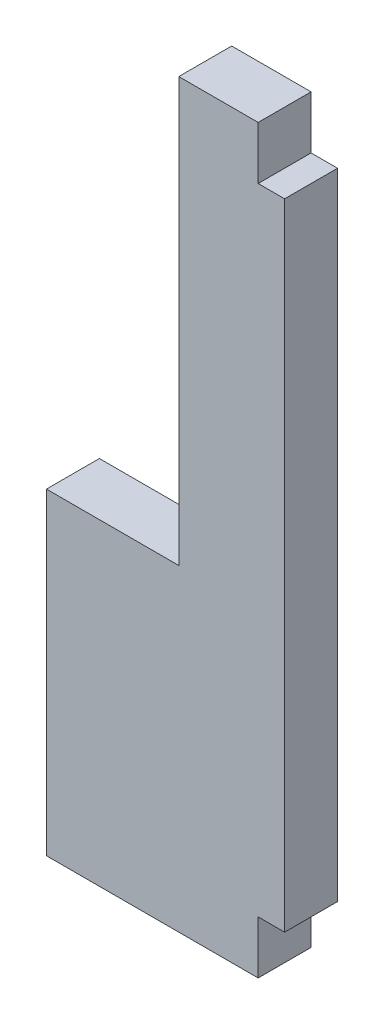
SolidWorks part; units mm, degrees
ref_plane "Front Plane" through (0, 0, 0) normal (0, 0, 1) x (1, 0, 0)
ref_plane "Top Plane" through (0, 0, 0) normal (0, 1, 0) x (1, 0, 0)
ref_plane "Right Plane" through (0, 0, 0) normal (1, 0, 0) x (0, 0, -1)
sketch "Sketch2" plane through (0, 0, 0) normal (0, 0, 1) x (1, 0, 0)
  line L0 (0, 120) -> (-5, 120)
  line L1 (-5, 120) -> (-5, 130)
  line L2 (-5, 130) -> (-20, 130)
  line L3 (-20, 130) -> (-20, 50)
  line L4 (-20, 50) -> (-45, 50)
  line L5 (-45, 50) -> (-45, -10)
  line L6 (-45, -10) -> (-5, -10)
  line L7 (-5, -10) -> (-5, 0)
  line L8 (-5, 0) -> (0, 0)
  line L9 (0, 0) -> (0, 120)
  point P2 (0, 0)
  dimension "D1" = 60
  dimension "D2" = 80
  dimension "D3" = 15
  dimension "D4" = 5
  dimension "D5" = 40
  dimension "D6" = 10
  dimension "D7" = 10
extrude "Boss-Extrude1" add sketch "Sketch2" along normal blind 10 contours L2 L3 L4 L5 L6 L7 L8 L9 L0 L1
